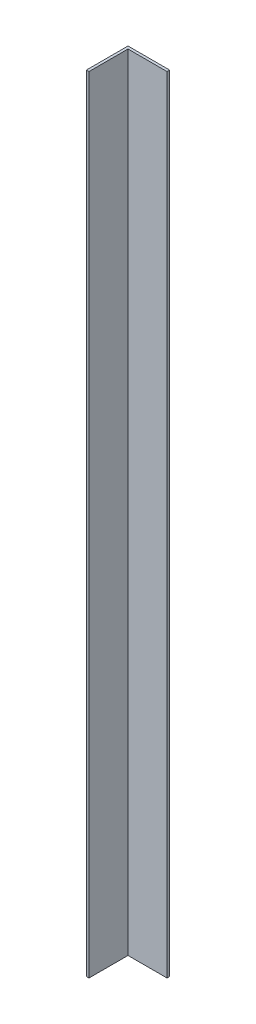
SolidWorks part; units mm, degrees
ref_plane "Front Plane" through (0, 0, 0) normal (0, 0, 1) x (1, 0, 0)
ref_plane "Top Plane" through (0, 0, 0) normal (0, 1, 0) x (1, 0, 0)
ref_plane "Right Plane" through (0, 0, 0) normal (1, 0, 0) x (0, 0, -1)
sketch "Sketch1" plane through (0, 0, 0) normal (0, 1, 0) x (1, 0, 0)
  line L1 (0, 0) -> (25.4, 0)
  line L2 (0, 0) -> (0, -25.4)
  line L3 (0, -25.4) -> (25.4, -25.4)
  line L4 (25.4, 0) -> (25.4, -25.4)
extrude "Boss-Extrude1" add sketch "Sketch1" along normal blind 479.425
sketch "Sketch2" plane through (0, 479.425, 0) normal (0, 1, 0) x (1, 0, 0)
  line L0 (25.4, -25.4) -> (25.4, 0) construction
  line L1 (25.4, -1.5875) -> (1.5875, -1.5875)
  line L2 (25.4, -1.5875) -> (25.4, -25.4)
  line L3 (25.4, -25.4) -> (1.5875, -25.4)
  line L4 (1.5875, -1.5875) -> (1.5875, -25.4)
  line L5 (0, -25.4) -> (25.4, -25.4) construction
  line L6 (25.4, 0) -> (0, 0) construction
  line L7 (0, 0) -> (0, -25.4) construction
  dimension "D1" = 1.5875
  dimension "D2" = 1.5875
extrude "Cut-Extrude1" cut sketch "Sketch2" against normal through all
